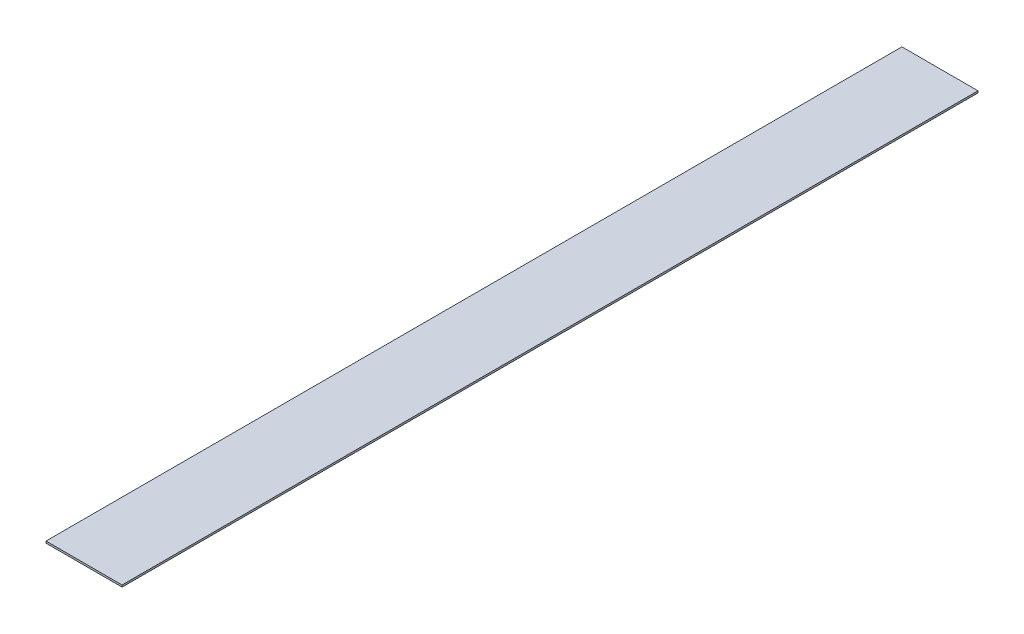
SolidWorks part; units mm, degrees
material "Nickel"
ref_plane "Front" through (0, 0, 0) normal (0, 0, 1) x (1, 0, 0)
ref_plane "Top" through (0, 0, 0) normal (0, 1, 0) x (1, 0, 0)
ref_plane "Right" through (0, 0, 0) normal (1, 0, 0) x (0, 0, -1)
sketch "Sketch1" plane through (0, 0, 0) normal (0, 0, 1) x (1, 0, 0)
  line L1 (-4, 0.1) -> (4, 0.1)
  line L2 (-4, 0.1) -> (-4, -0.1)
  line L3 (-4, -0.1) -> (4, -0.1)
  line L4 (4, 0.1) -> (4, -0.1)
  line L5 (-4, 0.1) -> (4, -0.1) construction
  line L6 (-4, -0.1) -> (4, 0.1) construction
  point P4 (0, 0)
  point P5 (0, 0)
  dimension "D1" = 8
  dimension "D2" = 0.2
extrude "Boss-Extrude1" add sketch "Sketch1" along normal blind 90
